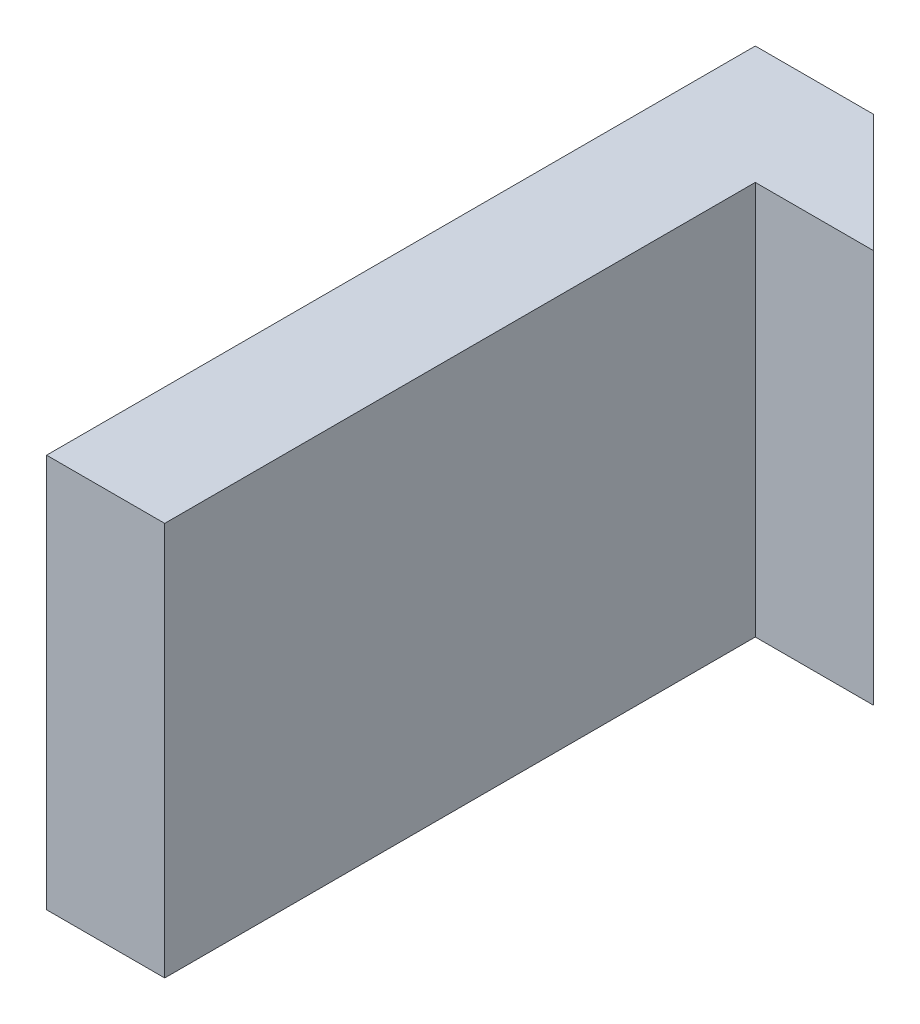
SolidWorks part; units mm, degrees
ref_plane "Front Plane" through (0, 0, 0) normal (0, 0, 1) x (1, 0, 0)
ref_plane "Top Plane" through (0, 0, 0) normal (0, 1, 0) x (1, 0, 0)
ref_plane "Right Plane" through (0, 0, 0) normal (1, 0, 0) x (0, 0, -1)
sketch "Sketch1" plane through (0, 0, 0) normal (0, 1, 0) x (1, 0, 0)
  line L0 (2.25, 6) -> (0.75, 7.5)
  line L1 (-0.75, 1.5) -> (0.75, 1.5)
  line L2 (-0.75, 1.5) -> (-0.75, -1.5)
  line L3 (-0.75, -1.5) -> (0.75, -1.5)
  line L4 (0.75, 1.5) -> (0.75, -1.5)
  line L5 (-0.75, 1.5) -> (0.75, -1.5) construction
  line L6 (-0.75, -1.5) -> (0.75, 1.5) construction
  line L7 (-0.75, 7.5) -> (0.75, 7.5)
  line L8 (-0.75, 7.5) -> (-0.75, 1.5)
  line L9 (-0.75, 1.5) -> (0.75, 1.5)
  line L10 (0.75, 6) -> (0.75, 1.5)
  line L11 (-0.75, 7.5) -> (0.75, 1.5) construction
  line L12 (-0.75, 1.5) -> (0.75, 7.5) construction
  line L13 (0.75, 6) -> (0.75, 7.5) construction
  line L15 (0.75, 6) -> (2.25, 6)
  point P0 (0, 0)
  point P6 (0, 4.5)
  dimension "D1" = 1.5
  dimension "D2" = 3
  dimension "D3" = 6
extrude "Boss-Extrude1" add sketch "Sketch1" along normal blind 5 contours L4 L1 L2 L3 | L10 L15 L0 L7 L8 L1
